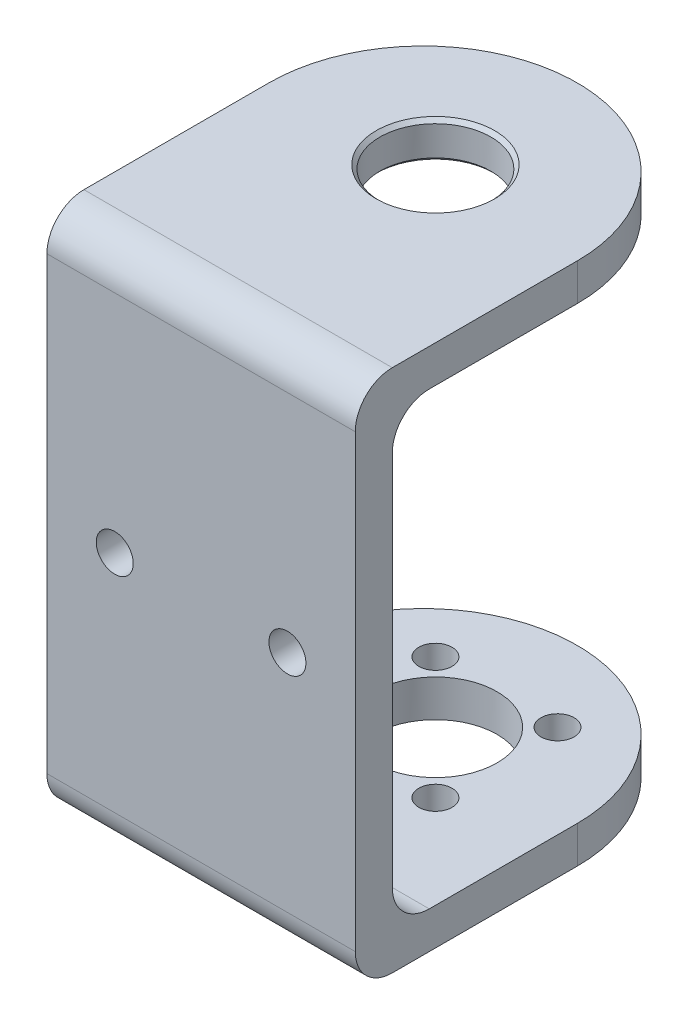
SolidWorks part; units mm, degrees
ref_plane "Front Plane" through (0, 0, 0) normal (0, 0, 1) x (1, 0, 0)
ref_plane "Top Plane" through (0, 0, 0) normal (0, 1, 0) x (1, 0, 0)
ref_plane "Right Plane" through (0, 0, 0) normal (1, 0, 0) x (0, 0, -1)
sketch "Sketch3" plane through (0, 0, 0) normal (0, 1, 0) x (1, 0, 0)
  line L1 (-12.5, 4) -> (12.5, 4)
  line L2 (-12.5, 4) -> (-12.5, 22)
  line L4 (12.5, 4) -> (12.5, 22)
  arc A0 (-12.5, 22) -> (12.5, 22) centre (0, 22) cw
  dimension "D1" = 4
  dimension "D2" = 25
  dimension "D4" = 18
extrude "Boss-Extrude3" add sketch "Sketch3" along normal mid plane 42.5
shell "Shell1" thickness 3
sketch "Sketch5" plane through (0, -18.25, 0) normal (0, -1, 0) x (1, 0, 0)
  circle A0 centre (0, -23) radius 7 construction
  dimension "D2" = 14
  dimension "D1" = 23
sketch "Sketch6" plane through (0, 21.25, 0) normal (0, 1, 0) x (1, 0, 0)
  circle A0 centre (0, 23) radius 4.5
  dimension "D1" = 9
  dimension "D2" = 23
sketch "Sketch7" plane through (0, 0, -7) normal (0, 0, -1) x (-1, 0, 0)
  circle A0 centre (-6.8718, 6.6437) radius 5.5509
extrude "Cut-Extrude3" [suppressed] cut sketch "Sketch7" against normal blind 10
extrude "Cut-Extrude4" cut sketch "Sketch6" against normal blind 8.5
sketch "Sketch8" plane through (0, -21.25, 0) normal (0, -1, 0) x (-1, 0, 0)
  line L0 (0, 23) -> (4.9497, 18.0503) construction
  line L1 (0, 23) -> (0, 0) construction
  circle A0 centre (4.9497, 18.0503) radius 1.3473
  circle A1 centre (-4.9497, 18.0503) radius 1.3473
  circle A2 centre (-4.9497, 27.9497) radius 1.3473
  circle A3 centre (4.9497, 27.9497) radius 1.3473
  circle A5 centre (0, 23) radius 7 construction
  point P15 (0, 23)
  dimension "D1" = 45
  dimension "D3" = 23
  dimension "D2" = 4
extrude "Cut-Extrude5" cut sketch "Sketch8" against normal blind 6
sketch "Sketch9" plane through (0, 0, -7) normal (0, 0, -1) x (-1, 0, 0)
  circle A0 centre (-7, 0) radius 1.5
  circle A1 centre (7, 0) radius 1.5
  dimension "D1" = 3
  dimension "D2" = 3
  dimension "D3" = 14
  dimension "D4" = 7
extrude "Cut-Extrude6" cut sketch "Sketch9" against normal blind 10
fillet "Fillet1" radius 3 4 edges at (0, -21.25, -4) (0, 21.25, -4) (0, 18.25, -7) (0, -18.25, -7)
sketch "Sketch11" plane through (0, -18.25, 0) normal (0, 1, 0) x (1, 0, 0)
  circle A0 centre (0, 23) radius 5
  circle A1 centre (0, 23) radius 4.5 construction
  dimension "D1" = 10
extrude "Cut-Extrude7" cut sketch "Sketch11" against normal blind 10
chamfer "Chamfer1" distance 0.3 angle 45 2 edges at (0, 18.25, -27.5) (0, 21.25, -18.5)
